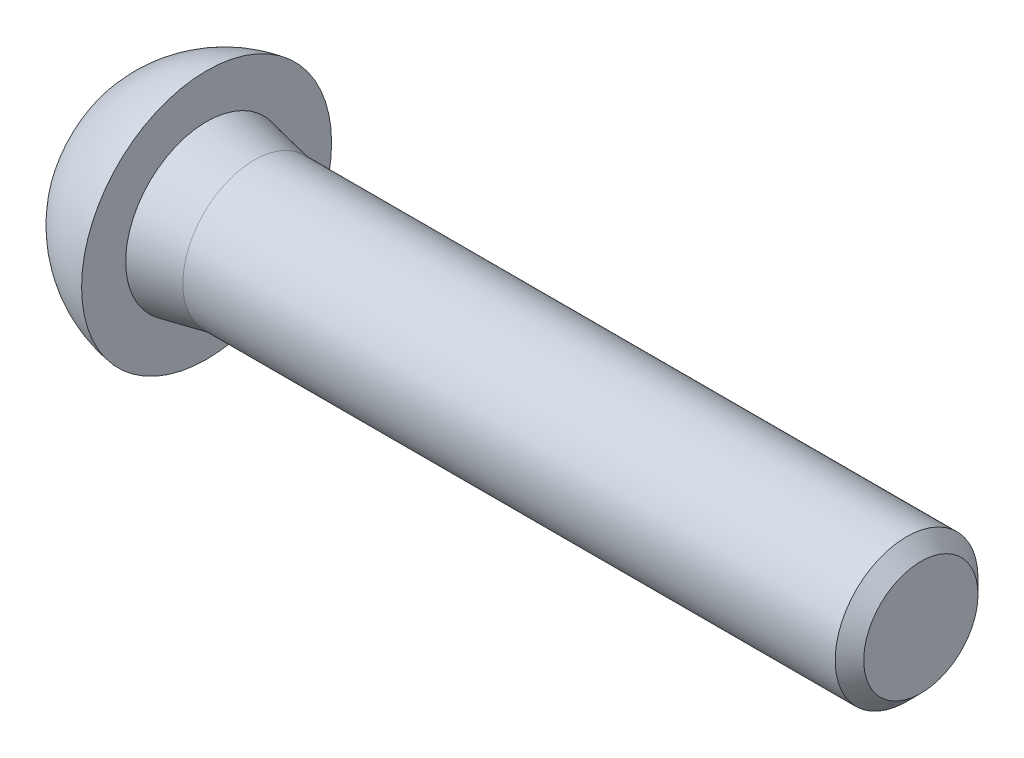
SolidWorks part; units mm, degrees
ref_plane "前视基准面" through (0, 0, 0) normal (0, 0, 1) x (1, 0, 0)
ref_plane "上视基准面" through (0, 0, 0) normal (0, 1, 0) x (1, 0, 0)
ref_plane "右视基准面" through (0, 0, 0) normal (1, 0, 0) x (0, 0, -1)
sketch "草图1" plane through (0, 0, 0) normal (0, 0, 1) x (1, 0, 0)
  line L0 (0, 0) -> (0, 3)
  line L1 (0, 3) -> (-28, 3)
  line L2 (-28, 3) -> (-30, 3.4)
  line L3 (-30, 3.4) -> (-30, 5.25)
  line L4 (0, 0) -> (-33.3, 0)
  line L5 (0, 0) -> (-159.9915, 0) construction
  line L6 (-33.3, 3.42) -> (-33.3, 0)
  arc A0 (-30, 5.25) -> (-33.3, 3.42) centre (-29.246, 0) ccw
  dimension "D2" = 30
  dimension "D1" = 6
  dimension "D3" = 6.8
  dimension "D4" = 10.5
  dimension "D5" = 2
  dimension "D6" = 6.84
  dimension "D7" = 3.3
revolve "旋转1" add sketch "草图1" angle 360 about L5
cosmetic thread "装饰螺纹线1" parameters "D2"=5.16
sketch "草图4" plane through (-33.3, 0, 0) normal (-1, 0, 0) x (0, 0, 1)
  line L1 (0, 2.3094) -> (-2, 1.1547)
  line L2 (-2, 1.1547) -> (-2, -1.1547)
  line L3 (-2, -1.1547) -> (0, -2.3094)
  line L4 (0, -2.3094) -> (2, -1.1547)
  line L5 (2, -1.1547) -> (2, 1.1547)
  line L6 (2, 1.1547) -> (0, 2.3094)
  circle A0 centre (0, 0) radius 2 construction
  dimension "D1" = 4
extrude "切除-拉伸1" cut sketch "草图4" against normal blind 2.08
chamfer "倒角1" distance 0.6 angle 45 1 edges at (0, 0, -3)
ref_plane "基准面2" through (-30.8075, 0, 0) normal (-1, 0, 0) x (0, 0, 1)
sketch "草图6" plane through (-31.22, 0, 0) normal (-1, 0, 0) x (0, 0, 1)
  line L1 (0, 2.3094) -> (-2, 1.1547)
  line L2 (-2, 1.1547) -> (-2, -1.1547)
  line L3 (-2, -1.1547) -> (0, -2.3094)
  line L4 (0, -2.3094) -> (2, -1.1547)
  line L5 (2, -1.1547) -> (2, 1.1547)
  line L6 (2, 1.1547) -> (0, 2.3094)
  circle A0 centre (0, 0) radius 2 construction
sketch "草图7" plane through (-30.8075, 0, 0) normal (-1, 0, 0) x (0, 0, 1)
  point P0 (0, 0)
loft "切除-放样1" cut profiles "草图7", "草图6"
